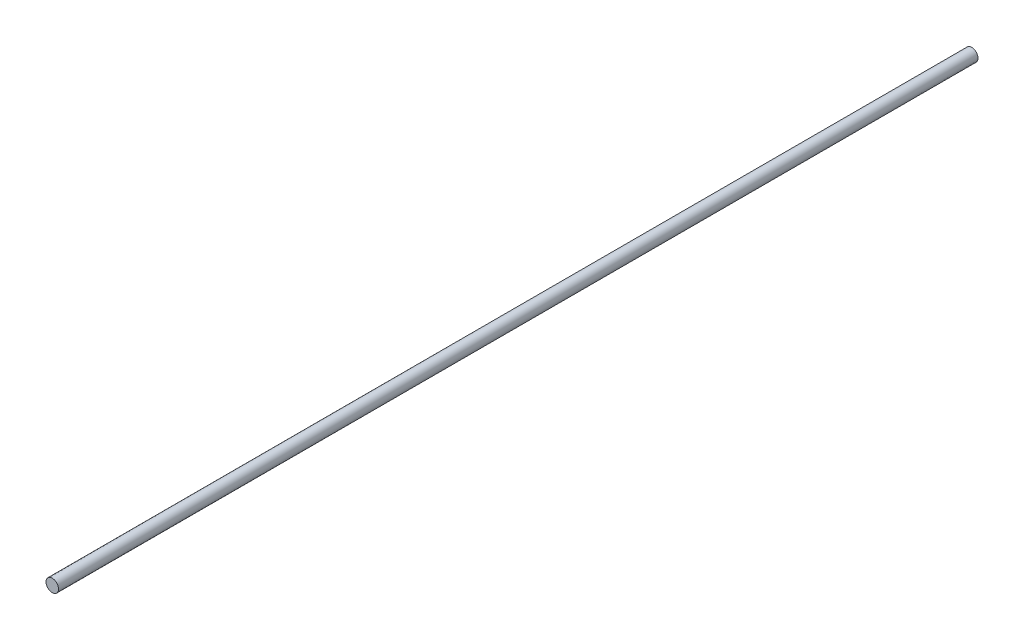
SolidWorks part; units mm, degrees
material "Plain Carbon Steel"
ref_plane "Front Plane" through (0, 0, 0) normal (0, 0, 1) x (1, 0, 0)
ref_plane "Top Plane" through (0, 0, 0) normal (0, 1, 0) x (1, 0, 0)
ref_plane "Right Plane" through (0, 0, 0) normal (1, 0, 0) x (0, 0, -1)
sketch "Sketch2" plane through (0, 0, 0) normal (0, 0, 1) x (1, 0, 0)
  circle A0 centre (0, 0) radius 6
  dimension "D1" = 12
extrude "Boss-Extrude1" add sketch "Sketch2" along normal mid plane 880
